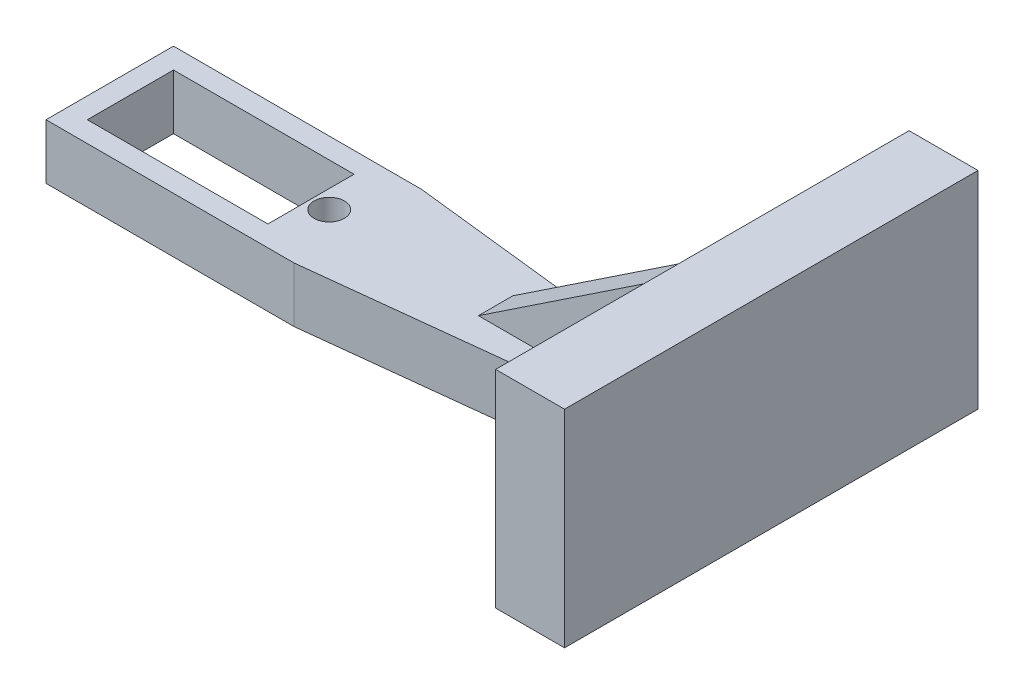
SolidWorks part; units mm, degrees
ref_plane "Front" through (0, 0, 0) normal (0, 0, 1) x (1, 0, 0)
ref_plane "Top" through (0, 0, 0) normal (0, 1, 0) x (1, 0, 0)
ref_plane "Right" through (0, 0, 0) normal (1, 0, 0) x (0, 0, -1)
sketch "草图1" plane through (0, 0, 0) normal (0, 1, 0) x (1, 0, 0)
  line L0 (0, 9.25) -> (0, -9.25) construction
  line L1 (-36, -9.25) -> (0, -9.25)
  line L2 (-36, -9.25) -> (-36, 9.25)
  line L3 (-36, 9.25) -> (0, 9.25)
  line L4 (0, 9.25) -> (0, -9.25)
  line L5 (-36, -9.25) -> (0, 0) construction
  line L6 (-36, 9.25) -> (0, 0) construction
  line L7 (-36, 0) -> (0, 0) construction
  line L8 (-18, 9.25) -> (-18, -9.25) construction
  line L10 (-6.8, 6.25) -> (-29.2, 6.25)
  line L11 (-6.8, 6.25) -> (-6.8, -6.25)
  line L12 (-6.8, -6.25) -> (-29.2, -6.25)
  line L14 (-6.8, 6.25) -> (-29.2, -6.25) construction
  line L15 (-6.8, -6.25) -> (-29.2, 6.25) construction
  line L16 (-29.2, 6.25) -> (-33, 6.25)
  line L20 (-29.2, -6.25) -> (-33, -6.25)
  line L21 (-33, 6.25) -> (-33, -6.25)
  point P0 (0, 0)
  point P12 (-18, 0)
  dimension "D2" = 18.5
  dimension "D3" = 18
  dimension "D4" = 22.4
  dimension "D5" = 12.5
  dimension "D6" = 3
extrude "凸台-拉伸1" add sketch "草图1" along normal blind 8
sketch "草图2" plane through (0, 8, 0) normal (0, 1, 0) x (1, 0, 0)
  line L3 (-18, 6.25) -> (-18, -6.25) construction
  line L4 (-6.8, 6.25) -> (-33, 6.25) construction
  line L5 (-33, -6.25) -> (-6.8, -6.25) construction
  line L6 (-6.8, -6.25) -> (-6.8, 6.25) construction
  line L7 (0, 9.25) -> (-36, 9.25) construction
  point P0 (-4.15, 0)
  dimension "D1" = 9.25
  dimension "D2" = 13.85
  dimension "D3" = 11.2
hole_wizard "M2 凹头盖螺钉的柱形沉头孔1" positions "3D草图1" profile "草图3" counterbore size "M2" standard "ANSI Metric" end condition up to next
sketch3d "3D草图1"
  point P0 (-4.15, 8, 0)
sketch "草图3" plane through (-4.15, 8, 0) normal (1, 0, 0) x (0, 0, 1)
  line L0 (0, 0) -> (0, 8)
  line L1 (0, 8) -> (1.2, 8)
  line L3 (1.2, 8) -> (1.2, 3.5)
  line L4 (1.2, 3.5) -> (2.2, 3.5)
  line L5 (2.2, 3.5) -> (2.2, 0)
  line L7 (2.2, 0) -> (0, 0)
  line L11 (0, -6.35) -> (0, 107.95) construction
  dimension "通孔孔直径" = 2.4
  dimension "通孔孔深度" = 8
  dimension "柱形沉头孔直径" = 4.4
  dimension "柱形沉头孔深度" = 3.5
sketch "草图4" plane through (0, 0, 0) normal (1, 0, 0) x (0, 0, -1)
  line L1 (9.25, 8) -> (-9.25, 8)
  line L2 (9.25, 8) -> (9.25, 0)
  line L3 (9.25, 0) -> (-9.25, 0)
  line L4 (-9.25, 8) -> (-9.25, 0)
ref_plane "基准面1" through (60, 0, 0) normal (1, 0, 0) x (0, 0, -1)
sketch "草图5" plane through (60, 0, 0) normal (1, 0, 0) x (0, 0, -1)
  line L0 (0, 8) -> (0, 0) construction
  line L1 (-9.25, 4) -> (9.25, 4) construction
  line L2 (-9.25, 8) -> (-9.25, 0) construction
  line L3 (9.25, 8) -> (9.25, 0) construction
  line L4 (9.25, 0) -> (-9.25, 0) construction
  line L5 (-2.5, 8) -> (2.5, 8)
  line L6 (-2.5, 8) -> (-2.5, 0)
  line L7 (-2.5, 0) -> (2.5, 0)
  line L8 (2.5, 8) -> (2.5, 0)
  line L9 (-2.5, 8) -> (2.5, 0) construction
  line L10 (-2.5, 0) -> (2.5, 8) construction
  point P10 (0, 4)
  dimension "D1" = 5
loft "放样1" add profiles "草图4", "草图5"
sketch "草图8" plane through (60, 0, 0) normal (1, 0, 0) x (0, 0, -1)
  line L0 (-30, 0) -> (30, 0)
  line L2 (-30, 0) -> (-30, 30)
  line L3 (-30, 30) -> (30, 30)
  line L4 (30, 0) -> (30, 30)
  line L5 (0, 0) -> (30, 30) construction
  line L6 (-30, 30) -> (0, 0) construction
  point P0 (0, 0)
  dimension "D1" = 30
  dimension "D2" = 60
  dimension "D3" = 30
extrude "凸台-拉伸2" add sketch "草图8" against normal blind 10
ref_plane "基准面2" through (0, 0, 0) normal (0, 0, 1) x (1, 0, 0)
sketch "草图11" plane through (0, 0, 0) normal (0, 0, 1) x (1, 0, 0)
  line L0 (50, 28) -> (20, 8)
  line L1 (50, 30) -> (50, 0) construction
  line L2 (0, 8) -> (50, 8) construction
  line L3 (50, 28) -> (50, 8)
  line L4 (50, 8) -> (20, 8)
  dimension "D1" = 30
  dimension "D2" = 20
extrude "凸台-拉伸3" add sketch "草图11" along normal mid plane 5
